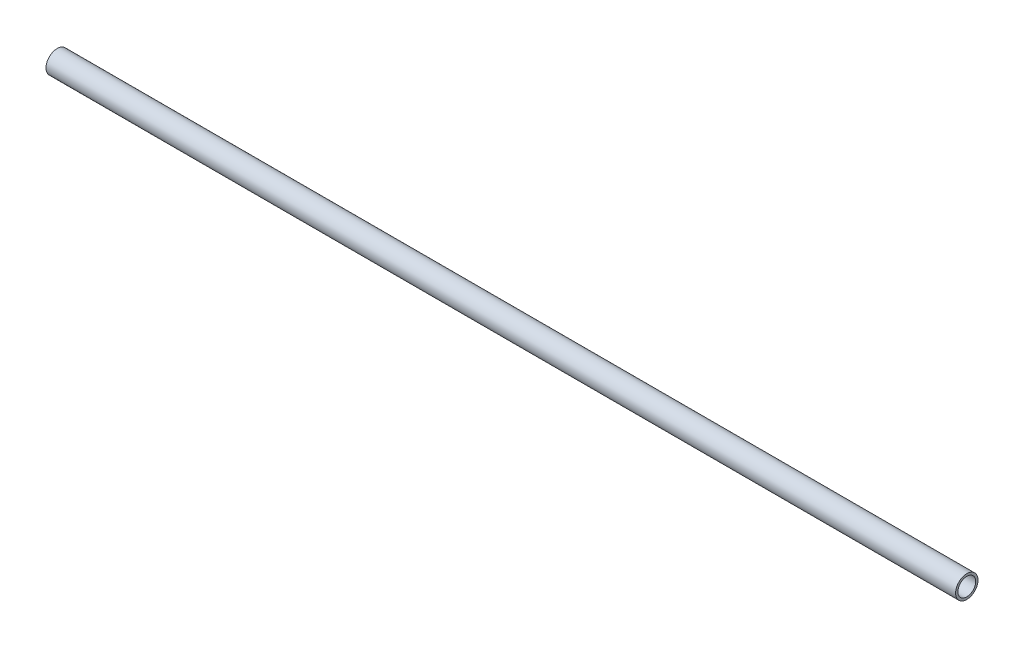
SolidWorks part; units mm, degrees
material "AISI 304"
ref_plane "Front Plane" through (0, 0, 0) normal (0, 0, 1) x (1, 0, 0)
ref_plane "Top Plane" through (0, 0, 0) normal (0, 1, 0) x (1, 0, 0)
ref_plane "Right Plane" through (0, 0, 0) normal (1, 0, 0) x (0, 0, -1)
sketch "Sketch1" plane through (0, 0, 0) normal (1, 0, 0) x (0, 0, -1)
  circle A0 centre (0, 0) radius 24.15
  circle A1 centre (0, 0) radius 19.15
  dimension "D1" = 48.3
  dimension "D2" = 38.3
extrude "Boss-Extrude1" add sketch "Sketch1" along normal mid plane 1960
